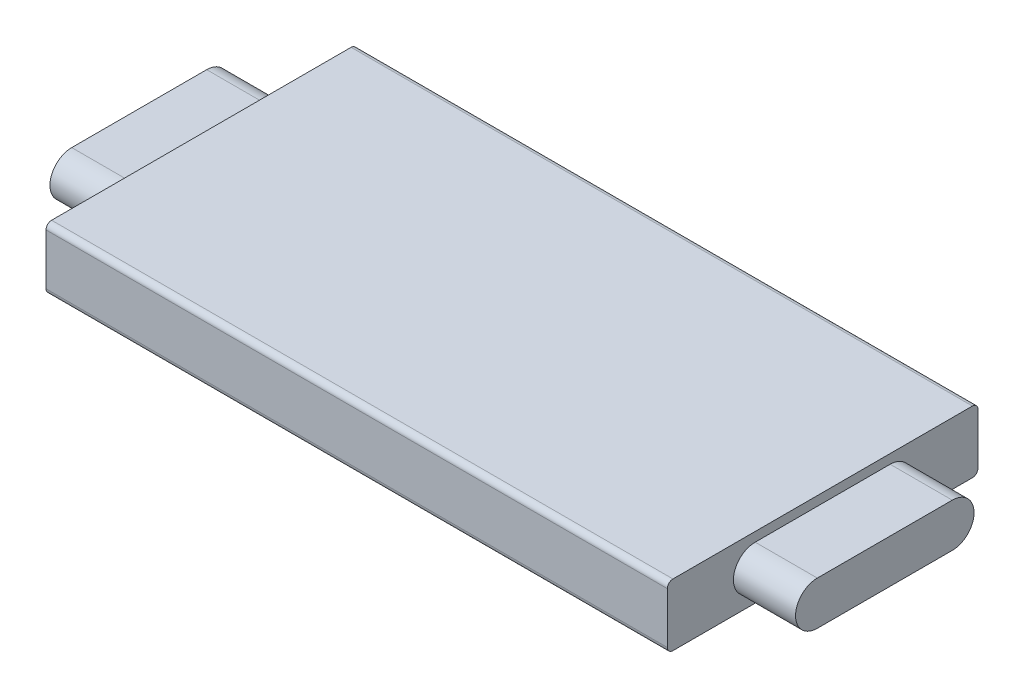
SolidWorks part; units mm, degrees
ref_plane "Front Plane" through (0, 0, 0) normal (0, 0, 1) x (1, 0, 0)
ref_plane "Top Plane" through (0, 0, 0) normal (0, 1, 0) x (1, 0, 0)
ref_plane "Right Plane" through (0, 0, 0) normal (1, 0, 0) x (0, 0, -1)
sketch "Sketch1" plane through (0, 0, 0) normal (0, 1, 0) x (1, 0, 0)
  line L1 (-12.7, -6.35) -> (12.7, -6.35)
  line L2 (-12.7, -6.35) -> (-12.7, 6.35)
  line L3 (-12.7, 6.35) -> (12.7, 6.35)
  line L4 (12.7, -6.35) -> (12.7, 6.35)
  line L5 (-12.7, -6.35) -> (12.7, 6.35) construction
  line L6 (-12.7, 6.35) -> (12.7, -6.35) construction
  point P0 (0, 0)
  dimension "D1" = 25.4
  dimension "D2" = 12.7
extrude "Boss-Extrude1" add sketch "Sketch1" along normal mid plane 2.54
fillet "Fillet1" radius 0.2286 4 edges at (0, -1.27, -6.35) (0, 1.27, -6.35) (0, -1.27, 6.35) (0, 1.27, 6.35)
sketch "Sketch3" plane through (0, 0, 0) normal (1, 0, 0) x (0, 0, -1)
  line L0 (-2.7585, 0) -> (2.7585, 0) construction
  line L1 (-2.7585, 0.8902) -> (2.7585, 0.8902)
  line L2 (-2.7585, -0.8902) -> (2.7585, -0.8902)
  arc A0 (-2.7585, 0.8902) -> (-2.7585, -0.8902) centre (-2.7585, 0) ccw
  arc A1 (2.7585, -0.8902) -> (2.7585, 0.8902) centre (2.7585, 0) ccw
  point P2 (0, 0)
extrude "Boss-Extrude2" add sketch "Sketch3" against normal offset from surface 2.54 and the other way offset from surface (15.24 mm away) 2.54 up to face at (-12.7, 0, 0) offset beyond the face yes other way up to face at (12.7, 0, 0)
